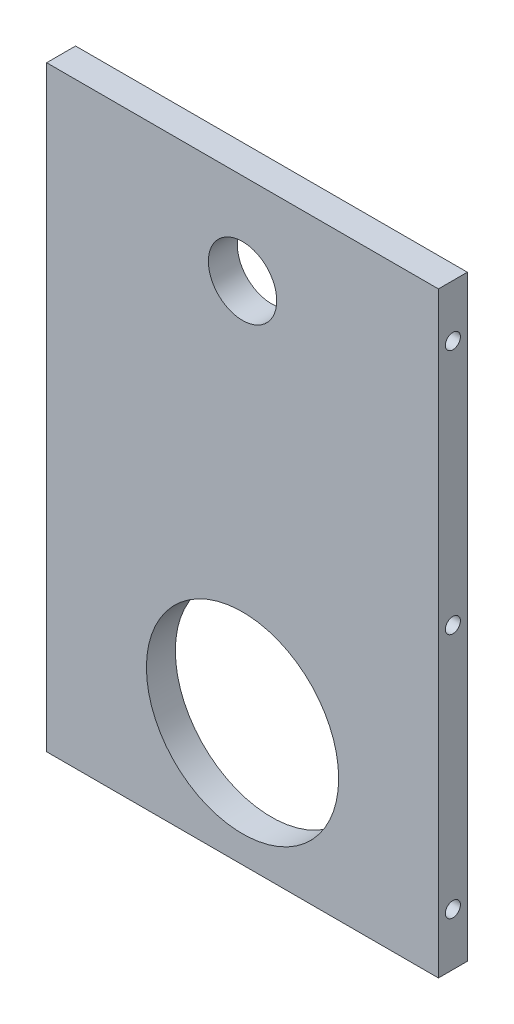
SolidWorks part; units mm, degrees
ref_plane "Front Plane" through (0, 0, 0) normal (0, 0, 1) x (1, 0, 0)
ref_plane "Top Plane" through (0, 0, 0) normal (0, 1, 0) x (1, 0, 0)
ref_plane "Right Plane" through (0, 0, 0) normal (1, 0, 0) x (0, 0, -1)
sketch "Sketch1" plane through (0, 0, 0) normal (0, 0, 1) x (1, 0, 0)
  line L1 (-43, -65.5) -> (43, -65.5)
  line L2 (-43, -65.5) -> (-43, 65.5)
  line L3 (-43, 65.5) -> (43, 65.5)
  line L4 (43, -65.5) -> (43, 65.5)
  line L5 (-43, -65.5) -> (43, 65.5) construction
  line L6 (-43, 65.5) -> (43, -65.5) construction
  point P0 (0, 0)
  dimension "D1" = 131
  dimension "D2" = 86
extrude "Boss-Extrude1" add sketch "Sketch1" along normal mid plane 6.35
sketch "Sketch2" plane through (-43, 0, 0) normal (-1, 0, 0) x (0, 0, 1)
  line L0 (0, 54) -> (0, -54) construction
  circle A0 centre (0, 54) radius 1.65
  circle A1 centre (0, -54) radius 1.65
  circle A2 centre (0, 0) radius 1.65
  point P7 (0, 0)
  dimension "D2" = 3.3
  dimension "D3" = 3.3
  dimension "D4" = 3.3
  dimension "D1" = 108
extrude "Cut-Extrude1" cut sketch "Sketch2" against normal blind 10 contours A0 | A2 | A1
mirror "Mirror1" about plane through (0, 0, 0) normal (1, 0, 0) of "Cut-Extrude1"
sketch "Sketch3" plane through (0, 0, 3.175) normal (0, 0, 1) x (1, 0, 0)
  line L0 (43, 65.5) -> (-43, 65.5) construction
  circle A0 centre (0, 45.5) radius 7.5
  point P2 (0, 0)
  point P3 (0, 0)
  dimension "D1" = 15
  dimension "D2" = 20
extrude "Cut-Extrude2" cut sketch "Sketch3" against normal through all contours A0
sketch "Sketch4" plane through (0, 0, 3.175) normal (0, 0, 1) x (1, 0, 0)
  circle A0 centre (0, -38.5) radius 21.1
  circle A1 centre (0, 45.5) radius 7.5 construction
  circle A2 centre (0, 45.5) radius 7.5
  point P2 (0, 0)
  point P4 (0, -37.4331)
  point P5 (0, 0)
  point P6 (0, 0)
  dimension "D1" = 42.2
  dimension "D2" = 84
extrude "Cut-Extrude3" cut sketch "Sketch4" against normal through all contours A0
